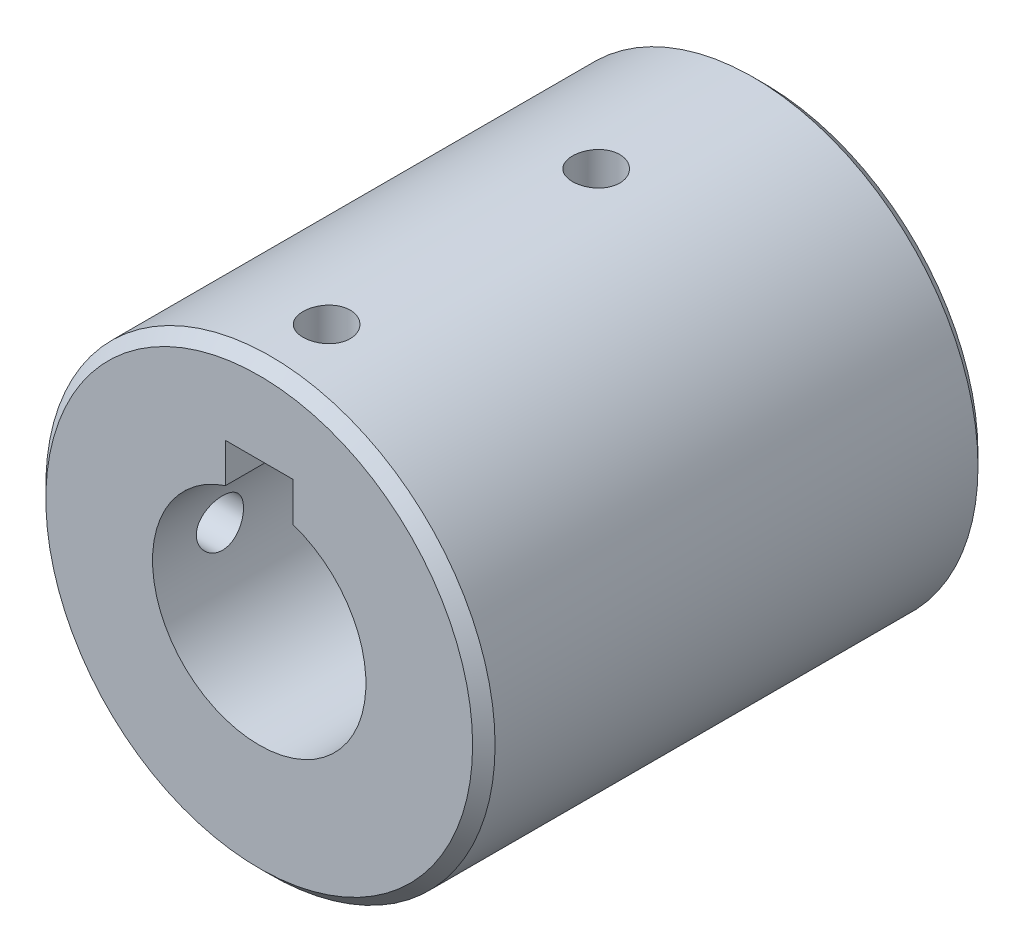
SolidWorks part; units mm, degrees
ref_plane "前视基准面" through (0, 0, 0) normal (0, 0, 1) x (1, 0, 0)
ref_plane "上视基准面" through (0, 0, 0) normal (0, 1, 0) x (1, 0, 0)
ref_plane "右视基准面" through (0, 0, 0) normal (1, 0, 0) x (0, 0, -1)
sketch "草图1" plane through (0, 0, 0) normal (0, 0, 1) x (1, 0, 0)
  circle A0 centre (0, 0) radius 9.5
  circle A1 centre (0, 0) radius 20
  dimension "D1" = 19
  dimension "D2" = 40
extrude "凸台-拉伸1" add sketch "草图1" along normal mid plane 45
sketch "草图3" plane through (0, 0, -22.5) normal (0, 0, -1) x (-1, 0, 0)
  line L0 (0, 0) -> (0, 20.6444) construction
  line L2 (-3, 6.5) -> (3, 6.5)
  line L3 (-3, 6.5) -> (-3, 12.5)
  line L4 (-3, 12.5) -> (3, 12.5)
  line L5 (3, 6.5) -> (3, 12.5)
  line L6 (-3, 6.5) -> (3, 12.5) construction
  line L7 (-3, 12.5) -> (3, 6.5) construction
  circle A1 centre (0, 0) radius 9.5 construction
  point P2 (0, 9.5)
  dimension "D1" = 6
  dimension "D2" = 6
extrude "切除-拉伸2" cut sketch "草图3" against normal through all
hole_wizard "M5 螺纹孔1" positions "3D草图1" profile "草图4" tap size "M5" standard "GB"
sketch3d "3D草图1"
  point P0 (-20, 0, 16.5)
  point P1 (-20, 0, -7.5)
  dimension "D1" = 6
  dimension "D2" = 30
cosmetic thread "孔螺蚊线1" parameters "D1"=10.735, "D2"=5
cosmetic thread "孔螺蚊线2" parameters "D1"=10.735, "D2"=5
sketch "草图4" plane through (-20, 0, 16.5) normal (0, 1, 0) x (0, 0, 1)
  line L0 (0, 0) -> (0, 20.2618)
  line L1 (0, 20.2618) -> (2.1, 19)
  line L2 (2.1, 19) -> (2.1, 0)
  line L5 (2.1, 0) -> (0, 0)
  line L10 (0, 20.2618) -> (-2.1, 19) construction
  line L11 (0, -6.35) -> (0, 107.95) construction
  dimension "螺纹孔钻头直径" = 4.2
  dimension "螺纹孔钻头深度" = 19
  dimension "导头角度" = 118
pattern_circular "阵列(圆周)1" count 2 every 90 about axis through (0, 0, 22.5) along (0, 0, -1) of "M5 螺纹孔1"
chamfer "倒角1" distance 1 angle 45 2 edges at (20, 0, -22.5) (20, 0, 22.5)
